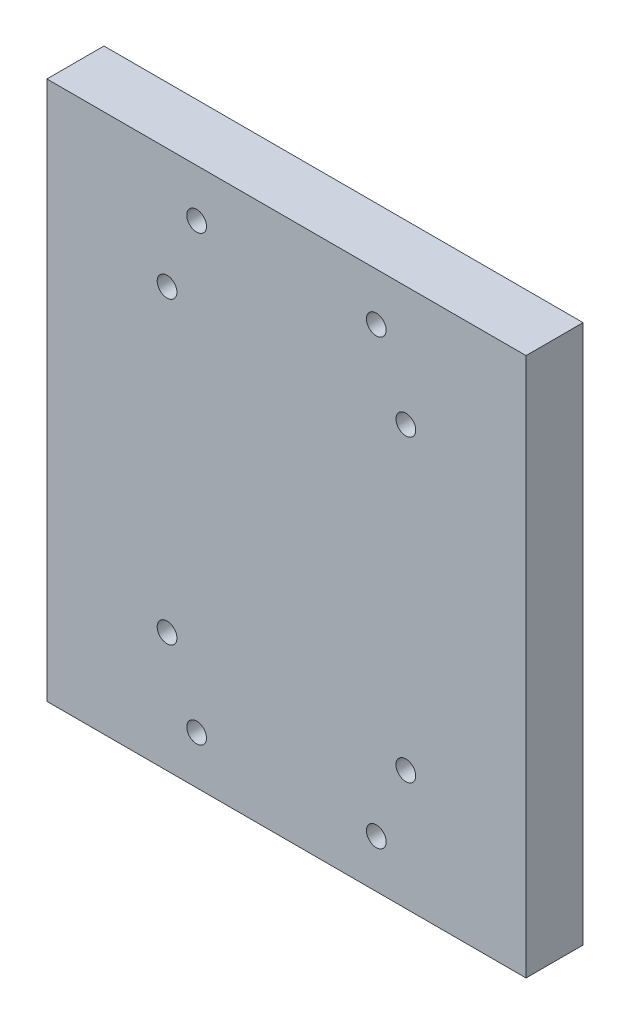
SolidWorks part; units mm, degrees
ref_plane "Front Plane" through (0, 0, 0) normal (0, 0, 1) x (1, 0, 0)
ref_plane "Top Plane" through (0, 0, 0) normal (0, 1, 0) x (1, 0, 0)
ref_plane "Right Plane" through (0, 0, 0) normal (1, 0, 0) x (0, 0, -1)
sketch "Sketch1" plane through (0, 0, 0) normal (0, 0, 1) x (1, 0, 0)
  line L1 (0, 0) -> (80, 0)
  line L2 (0, 0) -> (0, 90)
  line L3 (0, 90) -> (80, 90)
  line L4 (80, 0) -> (80, 90)
  circle A0 centre (55, 8) radius 1.65
  circle A1 centre (25, 8) radius 1.65
  circle A2 centre (55, 82) radius 1.65
  circle A3 centre (25, 82) radius 1.65
  dimension "D8" = 3.3
  dimension "D9" = 3.3
  dimension "D10" = 3.3
  dimension "D11" = 3.3
  dimension "D1" = 90
  dimension "D2" = 80
  dimension "D3" = 30
  dimension "D4" = 74
  dimension "D5" = 30
  dimension "D6" = 8
  dimension "D7" = 25
extrude "Boss-Extrude1" add sketch "Sketch1" along normal blind 9.53
sketch "Sketch2" plane through (0, 0, 9.53) normal (0, 0, 1) x (1, 0, 0)
  line L0 (40, 90) -> (40, 0) construction
  line L1 (80, 90) -> (0, 90) construction
  line L2 (0, 0) -> (80, 0) construction
  circle A0 centre (20.065, 20) radius 4.0314
  circle A1 centre (20.065, 70) radius 3.4601
  circle A2 centre (59.935, 70) radius 3.1456
  circle A3 centre (59.935, 20) radius 3.4793
  dimension "D1" = 39.87
  dimension "D2" = 39.87
  dimension "D3" = 19.935
  dimension "D4" = 20
  dimension "D5" = 20
hole_wizard "M4x0.7 Tapped Hole1" positions "3DSketch1" profile "Sketch3" tap size "M4x0.7" standard "Ansi Metric"
sketch3d "3DSketch1"
  point P0 (20.065, 70, 9.53)
  point P3 (20.065, 20, 9.53)
  point P6 (59.935, 20, 9.53)
  point P9 (59.935, 70, 9.53)
sketch "Sketch3" plane through (20.065, 70, 9.53) normal (1, 0, 0) x (0, -1, 0)
  line L0 (0, 0) -> (0, 11.0914)
  line L1 (0, 11.0914) -> (1.65, 10.1)
  line L2 (1.65, 10.1) -> (1.65, 0)
  line L5 (1.65, 0) -> (0, 0)
  line L10 (0, 11.0914) -> (-1.65, 10.1) construction
  line L11 (0, -6.35) -> (0, 107.95) construction
  dimension "Tap Drill Dia." = 3.3
  dimension "Tap Drill Depth" = 10.1
  dimension "Drill Angle" = 118
cosmetic thread "Hole Thread1" parameters "D1"=8, "D2"=4
cosmetic thread "Hole Thread2" parameters "D1"=8, "D2"=4
cosmetic thread "Hole Thread3" parameters "D1"=8, "D2"=4
cosmetic thread "Hole Thread4" parameters "D1"=8, "D2"=4
